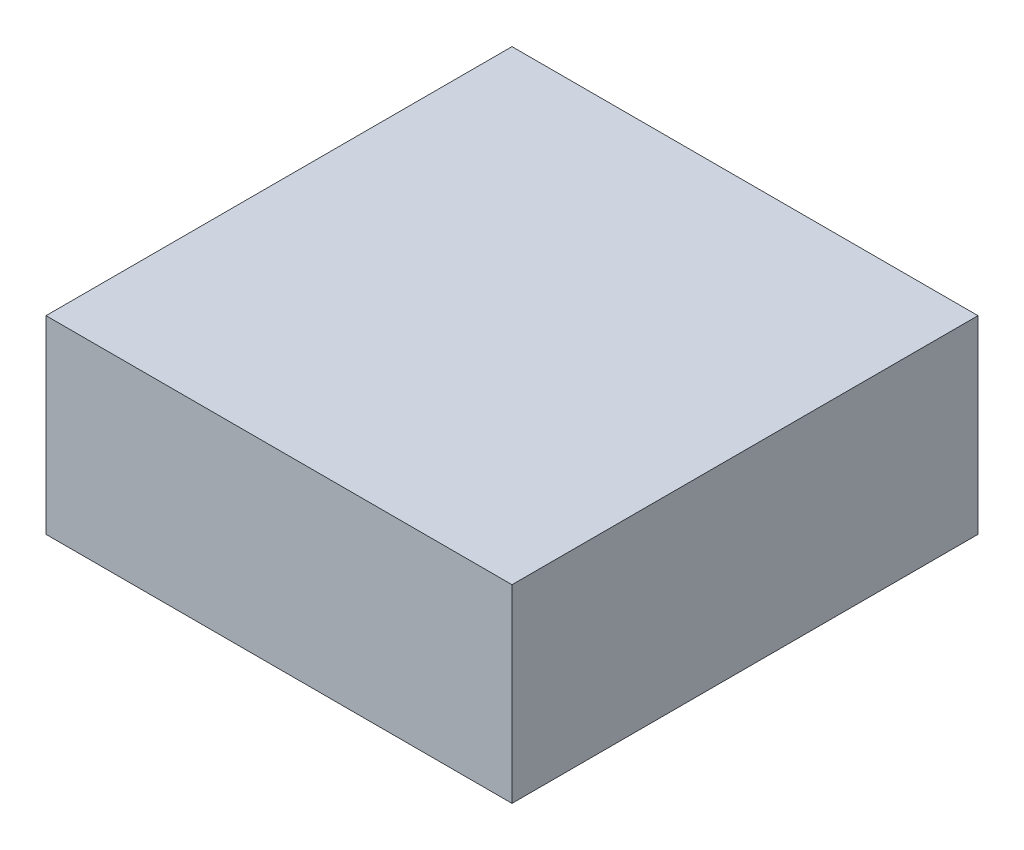
SolidWorks part; units mm, degrees
ref_plane "Front Plane" through (0, 0, 0) normal (0, 0, 1) x (1, 0, 0)
ref_plane "Top Plane" through (0, 0, 0) normal (0, 1, 0) x (1, 0, 0)
ref_plane "Right Plane" through (0, 0, 0) normal (1, 0, 0) x (0, 0, -1)
sketch "Sketch1" plane through (0, 0, 0) normal (0, 1, 0) x (1, 0, 0)
  line L1 (-7.75, -7.75) -> (7.75, -7.75)
  line L2 (-7.75, -7.75) -> (-7.75, 7.75)
  line L3 (-7.75, 7.75) -> (7.75, 7.75)
  line L4 (7.75, -7.75) -> (7.75, 7.75)
  line L5 (-7.75, -7.75) -> (7.75, 7.75) construction
  line L6 (-7.75, 7.75) -> (7.75, -7.75) construction
  point P0 (0, 0)
  dimension "D1" = 15.5
extrude "Boss-Extrude1" add sketch "Sketch1" along normal blind 6.3
